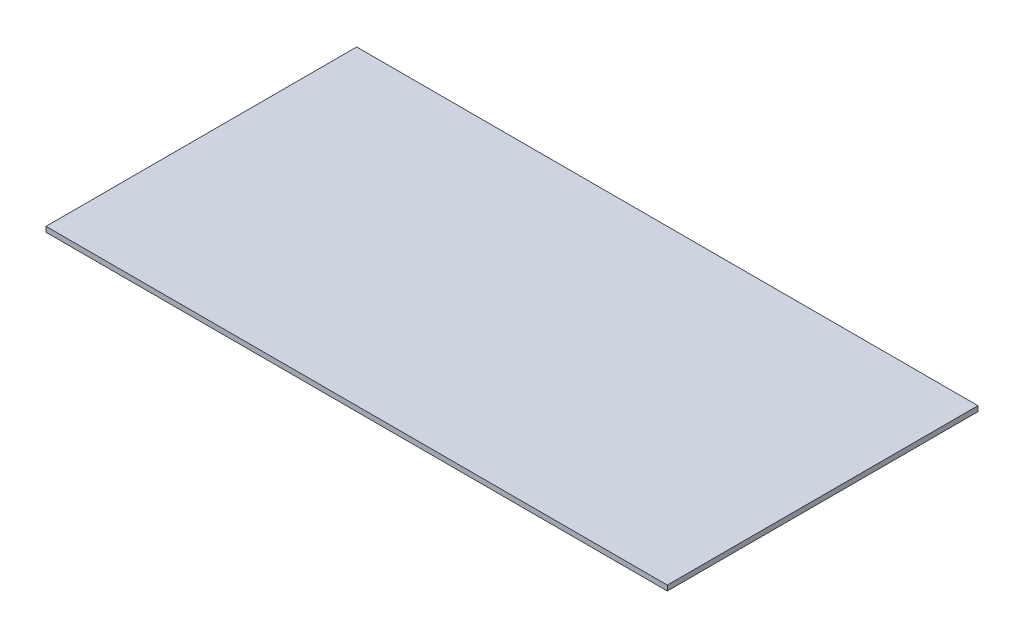
SolidWorks part; units mm, degrees
material "Д16Т ГОСТ 4784-97"
ref_plane "Front Plane" through (0, 0, 0) normal (0, 0, 1) x (1, 0, 0)
ref_plane "Top Plane" through (0, 0, 0) normal (0, 1, 0) x (1, 0, 0)
ref_plane "Right Plane" through (0, 0, 0) normal (1, 0, 0) x (0, 0, -1)
sketch "Sketch1" plane through (0, 0, 0) normal (0, 1, 0) x (1, 0, 0)
  line L1 (1500, 750) -> (-1500, 750)
  line L2 (1500, 750) -> (1500, -750)
  line L3 (1500, -750) -> (-1500, -750)
  line L4 (-1500, 750) -> (-1500, -750)
  line L5 (1500, 750) -> (-1500, -750) construction
  line L6 (1500, -750) -> (-1500, 750) construction
  point P0 (0, 0)
  dimension "D1" = 1500
  dimension "D2" = 3000
extrude "Boss-Extrude1" add sketch "Sketch1" along normal blind 25
